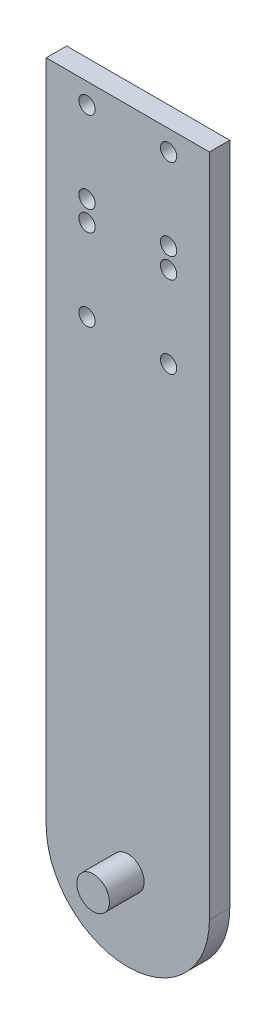
SolidWorks part; units mm, degrees
ref_plane "Front Plane" through (0, 0, 0) normal (0, 0, 1) x (1, 0, 0)
ref_plane "Top Plane" through (0, 0, 0) normal (0, 1, 0) x (1, 0, 0)
ref_plane "Right Plane" through (0, 0, 0) normal (1, 0, 0) x (0, 0, -1)
sketch "Sketch1" plane through (0, 0, 0) normal (0, 0, 1) x (1, 0, 0)
  line L0 (-40, 163) -> (0, 163)
  line L2 (0, 0) -> (0, 163)
  line L4 (-40, 0) -> (-40, 163)
  arc A0 (-40, 0) -> (0, 0) centre (-20, 0) ccw
  dimension "D1" = 40
  dimension "D2" = 163
extrude "Boss-Extrude1" add sketch "Sketch1" along normal blind 5
sketch "Sketch2" plane through (0, 0, 5) normal (0, 0, 1) x (1, 0, 0)
  circle A0 centre (-20, 0) radius 4
  dimension "D1" = 8
extrude "Boss-Extrude2" add sketch "Sketch2" along normal blind 8.5
sketch "Sketch3" plane through (0, 0, 5) normal (0, 0, 1) x (1, 0, 0)
  line L0 (-20, 163) -> (-10, 163)
  line L1 (0, 163) -> (-40, 163) construction
  line L2 (-20, 163) -> (-30, 163)
  line L3 (-30, 163) -> (-30, 158)
  line L4 (-10, 163) -> (-10, 158)
  circle A0 centre (-30, 158) radius 2
  circle A1 centre (-10, 158) radius 2
  dimension "D5" = 4
  dimension "D6" = 4
  dimension "D1" = 10
  dimension "D2" = 10
  dimension "D3" = 5
  dimension "D4" = 5
extrude "Cut-Extrude1" cut sketch "Sketch3" against normal blind 50
sketch "Sketch5" plane through (0, 0, 5) normal (0, 0, 1) x (1, 0, 0)
  line L0 (-20, 163) -> (-30, 163)
  line L1 (0, 163) -> (-40, 163) construction
  line L2 (-20, 163) -> (-10, 163)
  line L3 (-30, 163) -> (-30, 133)
  line L4 (-10, 163) -> (-10, 133)
  circle A0 centre (-30, 133) radius 2
  circle A1 centre (-10, 133) radius 2
  dimension "D5" = 4
  dimension "D6" = 4
  dimension "D1" = 10
  dimension "D2" = 10
  dimension "D3" = 30
  dimension "D4" = 30
extrude "Cut-Extrude2" cut sketch "Sketch5" against normal blind 50
pattern_linear "LPattern1" count 2 spacing 20 along (0, -1, 0) of "Cut-Extrude1", "Cut-Extrude2"
